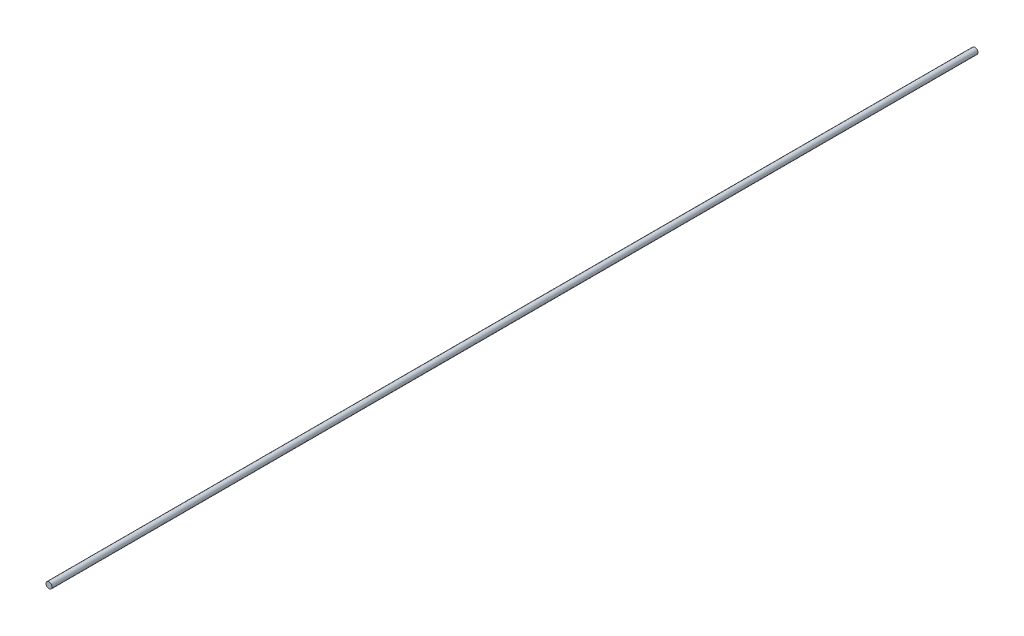
SolidWorks part; units mm, degrees
material "Hexcel AS4C (3000 Filaments)"
ref_plane "Front Plane" through (0, 0, 0) normal (0, 0, 1) x (1, 0, 0)
ref_plane "Top Plane" through (0, 0, 0) normal (0, 1, 0) x (1, 0, 0)
ref_plane "Right Plane" through (0, 0, 0) normal (1, 0, 0) x (0, 0, -1)
sketch "Sketch1" plane through (0, 0, 0) normal (0, 0, 1) x (1, 0, 0)
  circle A0 centre (0, 0) radius 2
extrude "Boss-Extrude1" add sketch "Sketch1" along normal blind 610
